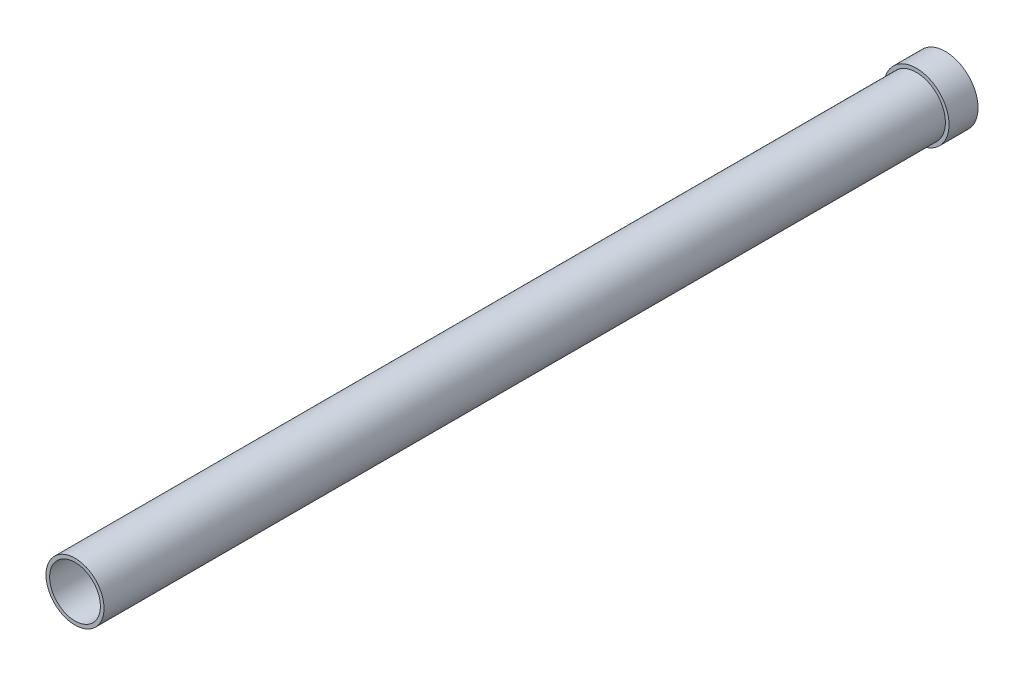
SolidWorks part; units mm, degrees
ref_plane "Front Plane" through (0, 0, 0) normal (0, 0, 1) x (1, 0, 0)
ref_plane "Top Plane" through (0, 0, 0) normal (0, 1, 0) x (1, 0, 0)
ref_plane "Right Plane" through (0, 0, 0) normal (1, 0, 0) x (0, 0, -1)
sketch "Sketch1" plane through (0, 0, 0) normal (0, 0, 1) x (1, 0, 0)
  circle A0 centre (0, 0) radius 2.54
  circle A1 centre (0, 0) radius 2.2225
extrude "Boss-Extrude1" add sketch "Sketch1" along normal blind 76.2
sketch "Sketch2" plane through (0, 0, 0) normal (0, 0, -1) x (-1, 0, 0)
  circle A0 centre (0, 0) radius 2.8575
  circle A1 centre (0, 0) radius 2.54
extrude "Boss-Extrude2" add sketch "Sketch2" against normal blind 2.54
